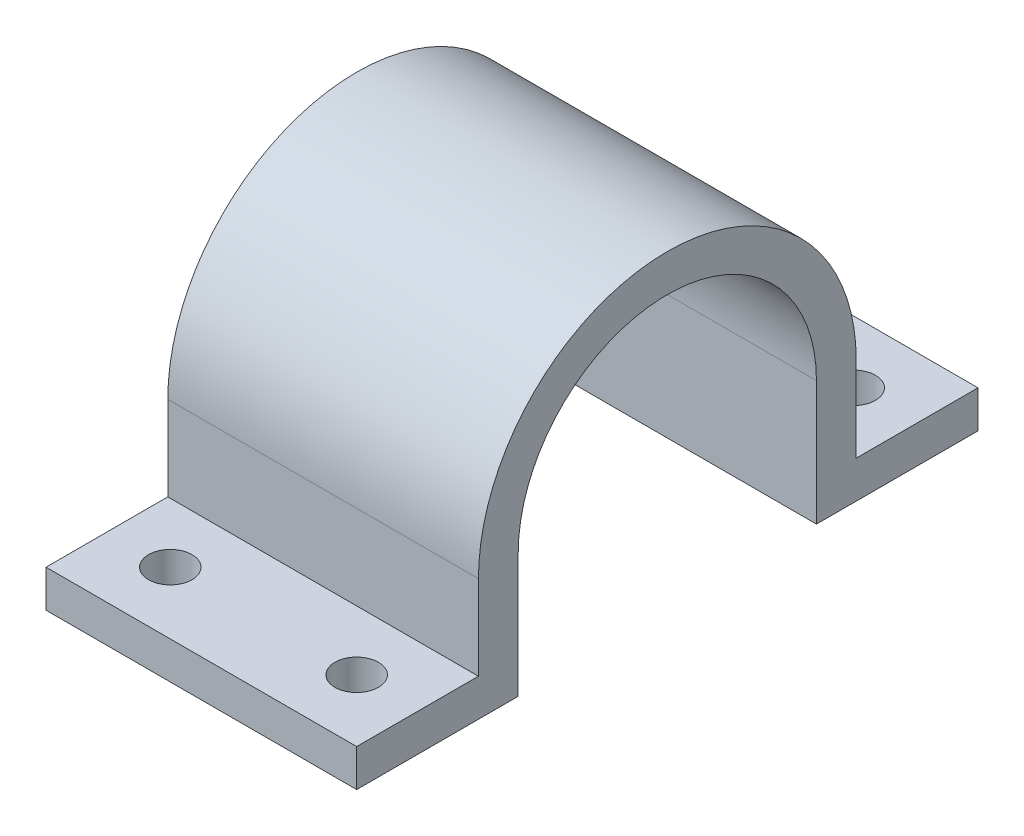
SolidWorks part; units mm, degrees
ref_plane "Front Plane" through (0, 0, 0) normal (0, 0, 1) x (1, 0, 0)
ref_plane "Top Plane" through (0, 0, 0) normal (0, 1, 0) x (1, 0, 0)
ref_plane "Right Plane" through (0, 0, 0) normal (1, 0, 0) x (0, 0, -1)
sketch "Sketch1" plane through (0, 0, 0) normal (1, 0, 0) x (0, 0, -1)
  line L0 (-25, 0) -> (-25, 3)
  line L1 (55, 0) -> (-55, 0) construction
  line L3 (-25, 3) -> (25, 3) construction
  line L5 (25, 3) -> (25, 0)
  line L6 (25, 0) -> (-25, 0)
  line L7 (0, 55) -> (0, -55) construction
  line L8 (0, 25) -> (0, 0) construction
  line L9 (-15.2, 9.8) -> (-15.2, 3)
  line L13 (-25, 3) -> (-15.2, 3)
  line L15 (15.2, 9.8) -> (15.2, 3)
  line L16 (15.2, 3) -> (25, 3)
  arc A1 (-15.2, 9.8) -> (15.2, 9.8) centre (0, 9.8) cw
  dimension "D3" = 15.2
  dimension "D4" = 25
  dimension "D1" = 50
  dimension "D2" = 3
  dimension "D5" = 25
extrude "Boss-Extrude1" add sketch "Sketch1" along normal blind 25
sketch "Sketch2" plane through (25, 0, 0) normal (1, 0, 0) x (0, 0, -1)
  line L0 (-12, 10) -> (-12, 0)
  line L1 (13.75, 0) -> (-13.75, 0) construction
  line L2 (12, 10) -> (12, 0)
  line L5 (-12, 0) -> (12, 0)
  line L6 (0, 13.75) -> (0, -13.75) construction
  line L7 (0, 22) -> (0, 0) construction
  arc A2 (-12, 10) -> (12, 10) centre (0, 10) cw
  dimension "D1" = 22
  dimension "D3" = 12
extrude "Cut-Extrude1" cut sketch "Sketch2" against normal through all
sketch "Sketch3" plane through (0, 3, 0) normal (0, 1, 0) x (1, 0, 0)
  line L0 (25, 25) -> (25, 15.2) construction
  line L1 (25, 25) -> (0, 25) construction
  line L2 (25, -25) -> (0, -25) construction
  circle A0 centre (5, -20) radius 1.75
  circle A1 centre (20, -20) radius 1.75
  circle A2 centre (5, 20) radius 1.75
  circle A3 centre (20, 20) radius 1.75
  dimension "D1" = 3.5
  dimension "D2" = 15
  dimension "D3" = 5
  dimension "D4" = 5
  dimension "D5" = 5
extrude "Cut-Extrude2" cut sketch "Sketch3" against normal through all
